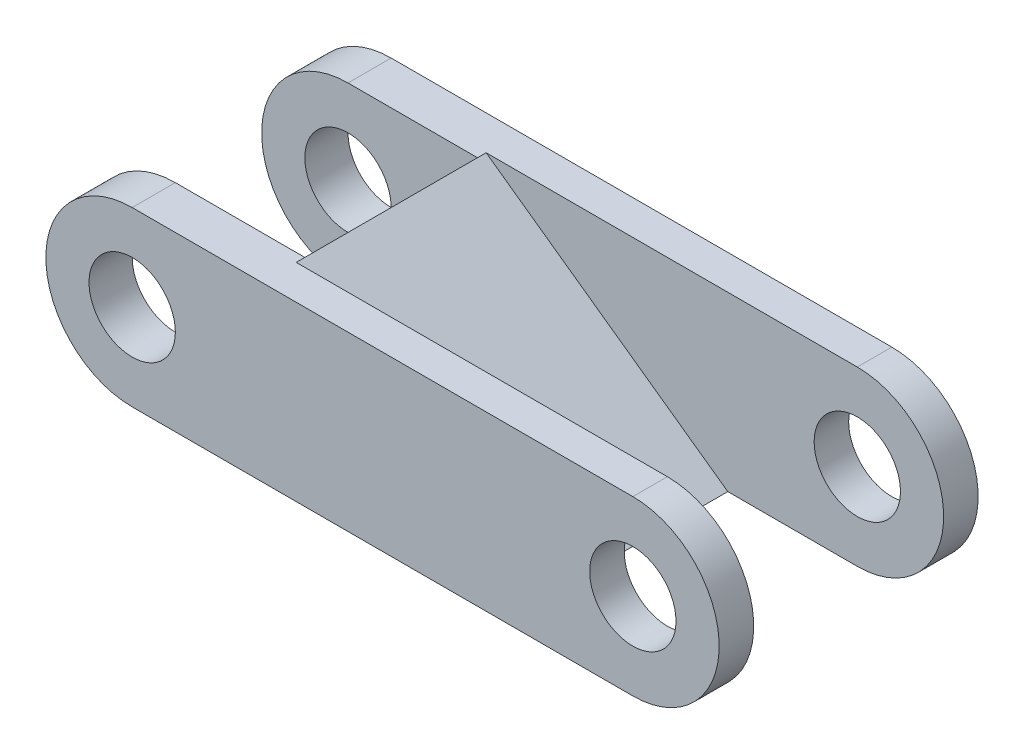
SolidWorks part; units mm, degrees
ref_plane "Front Plane" through (0, 0, 0) normal (0, 0, 1) x (1, 0, 0)
ref_plane "Top Plane" through (0, 0, 0) normal (0, 1, 0) x (1, 0, 0)
ref_plane "Right Plane" through (0, 0, 0) normal (1, 0, 0) x (0, 0, -1)
sketch "Sketch1" plane through (0, 0, 0) normal (0, 0, 1) x (1, 0, 0)
  line L0 (0, 0) -> (57.9939, 0) construction
  line L1 (0, 10) -> (57.9939, 10)
  line L2 (0, -10) -> (57.9939, -10)
  arc A0 (0, 10) -> (0, -10) centre (0, 0) ccw
  arc A1 (57.9939, -10) -> (57.9939, 10) centre (57.9939, 0) ccw
  circle A2 centre (0, 0) radius 5
  circle A3 centre (57.9939, 0) radius 5
  point P3 (28.9969, 0)
  dimension "D1" = 10
  dimension "D2" = 10
  dimension "D3" = 20
extrude "Boss-Extrude1" add sketch "Sketch1" along normal blind 30
sketch "Sketch2" plane through (0, 10, 0) normal (0, 1, 0) x (1, 0, 0)
  line L0 (-10, 0) -> (-10, -30) construction
  line L1 (15, -5) -> (-10, -5)
  line L2 (15, -5) -> (15, -25)
  line L3 (15, -25) -> (-10, -25)
  line L4 (-10, -5) -> (-10, -25)
  line L5 (67.9939, -30) -> (67.9939, 0) construction
  line L6 (0, -30) -> (0, 0) construction
  line L15 (42.9939, -26) -> (67.9939, -26)
  line L16 (42.9939, -26) -> (42.9939, -4)
  line L17 (42.9939, -4) -> (67.9939, -4)
  line L18 (67.9939, -26) -> (67.9939, -4)
  line L19 (57.9939, -30) -> (57.9939, 0) construction
  point P7 (-10, -15)
  point P10 (0, -15)
  point P15 (67.9939, -15)
  point P19 (57.9939, -15)
  dimension "D1" = 20
  dimension "D2" = 25
  dimension "D3" = 22
  dimension "D4" = 25
extrude "Cut-Extrude1" cut sketch "Sketch2" against normal through all
sketch "Sketch4" plane through (0, 0, 5) normal (0, 0, 1) x (1, 0, 0)
  line L0 (15, 10) -> (42.9939, 10)
  line L1 (42.9939, 10) -> (42.9939, -10)
  line L2 (42.9939, -10) -> (15, 10)
extrude "Cut-Extrude2" cut sketch "Sketch4" along normal up to surface (20 mm away) up to face at (5, 0, 25)
sketch "Sketch5" plane through (0, 0, 5) normal (0, 0, 1) x (1, 0, 0)
  line L3 (15, 10) -> (42.9939, -10)
  line L4 (42.9939, -10) -> (42.9939, 10)
  line L5 (42.9939, 10) -> (15, 10)
  line L6 (15, 10) -> (42.9939, -10)
  line L7 (42.9939, -10) -> (42.9939, 10)
  line L8 (42.9939, 10) -> (15, 10)
  dimension "D1" = 0
extrude "Cut-Extrude3" cut sketch "Sketch5" against normal up to surface and the other way up to surface up to face at (52.9939, 0, 4) other way up to face at (62.9939, 0, 26)
